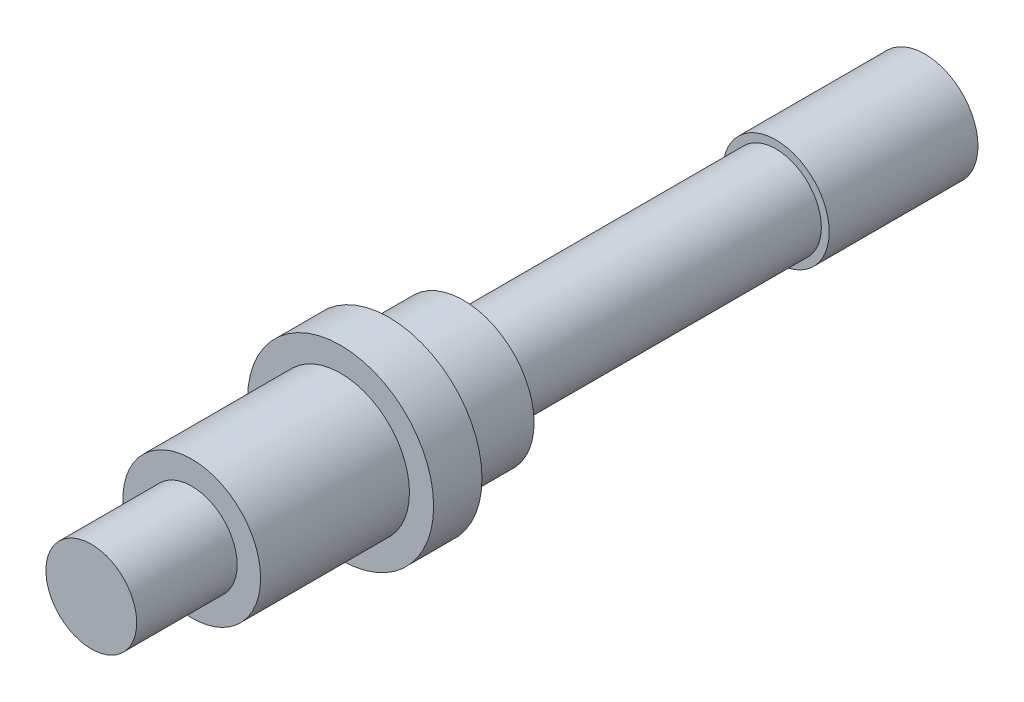
SolidWorks part; units mm, degrees
ref_plane "Front" through (0, 0, 0) normal (0, 0, 1) x (1, 0, 0)
ref_plane "Top" through (0, 0, 0) normal (0, 1, 0) x (1, 0, 0)
ref_plane "Right" through (0, 0, 0) normal (1, 0, 0) x (0, 0, -1)
sketch "Sketch1" plane through (0, 0, 0) normal (0, 1, 0) x (1, 0, 0)
  line L0 (0, 0) -> (14.3, 0)
  line L1 (14.3, 0) -> (14.3, -40)
  line L2 (14.3, -40) -> (12.2, -40)
  line L3 (12.2, -40) -> (12.2, -124)
  line L13 (0, -139.0124) -> (0, 0)
  line L14 (12.2, -124) -> (19, -124)
  line L15 (19, -124) -> (19, -144)
  line L16 (19, -144) -> (25, -144)
  line L17 (25, -144) -> (25, -157)
  line L18 (25, -157) -> (18.5, -157)
  line L19 (18.5, -157) -> (18.5, -197)
  line L20 (18.5, -197) -> (12.2, -197)
  line L21 (12.2, -197) -> (12.2, -224)
  line L22 (12.2, -224) -> (0, -224)
  line L23 (0, -224) -> (0, -139.0124)
  dimension "D1" = 14.3
  dimension "D2" = 12.2
  dimension "D3" = 40
  dimension "D4" = 20
  dimension "D5" = 19
  dimension "D6" = 25
  dimension "D7" = 13
  dimension "D8" = 18.5
  dimension "D9" = 40
  dimension "D10" = 27
  dimension "D11" = 12.2
revolve "Revolve1" add sketch "Sketch1" angle 360 about L13
